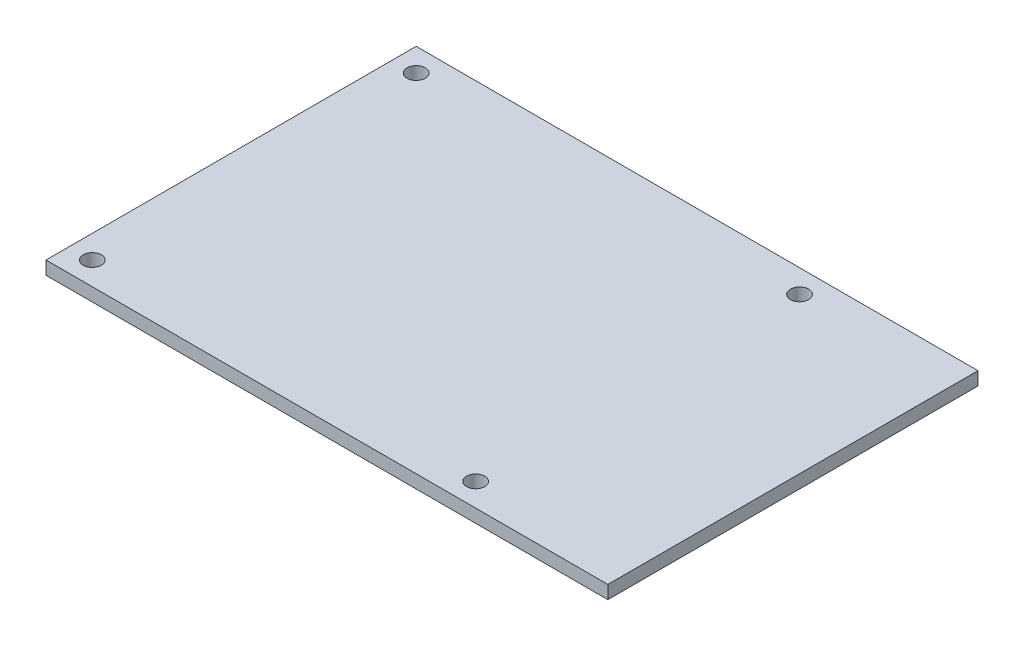
SolidWorks part; units mm, degrees
ref_plane "Plano frontal" through (0, 0, 0) normal (0, 0, 1) x (1, 0, 0)
ref_plane "Plano superior" through (0, 0, 0) normal (0, 1, 0) x (1, 0, 0)
ref_plane "Plano direito" through (0, 0, 0) normal (1, 0, 0) x (0, 0, -1)
sketch "Esboço1" plane through (0, 0, 0) normal (0, 1, 0) x (1, 0, 0)
  line L1 (-42.5, 28) -> (42.5, 28)
  line L2 (-42.5, 28) -> (-42.5, -28)
  line L3 (-42.5, -28) -> (42.5, -28)
  line L4 (42.5, 28) -> (42.5, -28)
  line L5 (-42.5, 28) -> (42.5, -28) construction
  line L6 (-42.5, -28) -> (42.5, 28) construction
  circle A0 centre (-39, -24.5) radius 1.375
  circle A1 centre (-39, 24.5) radius 1.375
  circle A2 centre (19, -24.5) radius 1.375
  circle A3 centre (19, 24.5) radius 1.375
  point P0 (0, 0)
  dimension "D3" = 2.75
  dimension "D10" = 3.5
  dimension "D4" = 3.5
  dimension "D5" = 3.5
  dimension "D6" = 58
  dimension "D11" = 2.75
  dimension "D1" = 85
  dimension "D2" = 56
  dimension "D7" = 3.5
  dimension "D8" = 3.5
  dimension "D9" = 58
  dimension "D12" = 3.5
extrude "Ressalto-extrusão1" add sketch "Esboço1" along normal blind 2
